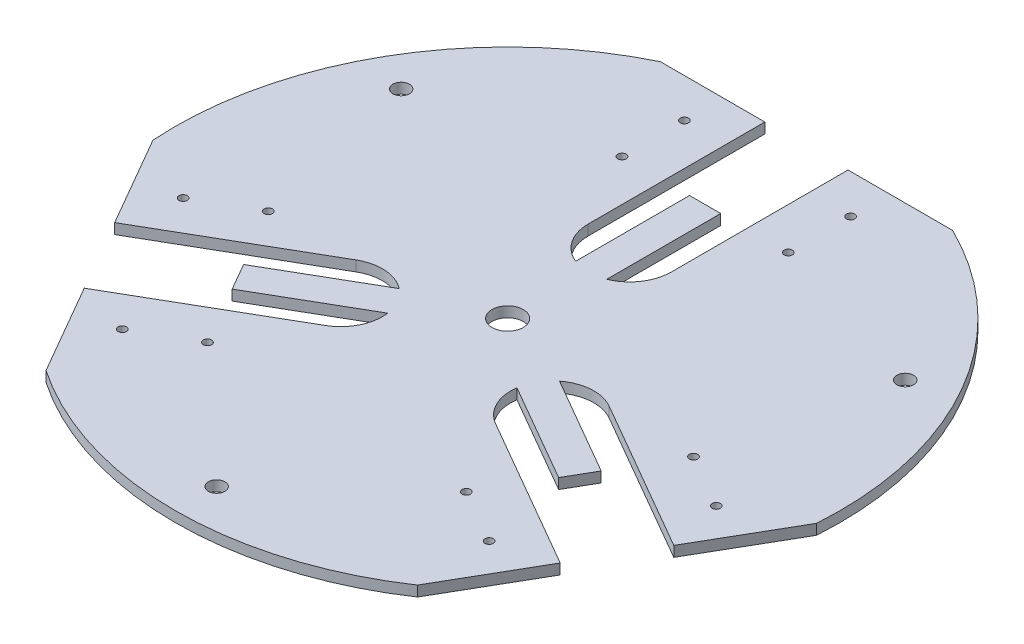
SolidWorks part; units mm, degrees
ref_plane "Front Plane" through (0, 0, 0) normal (0, 0, 1) x (1, 0, 0)
ref_plane "Top Plane" through (0, 0, 0) normal (0, 1, 0) x (1, 0, 0)
ref_plane "Right Plane" through (0, 0, 0) normal (1, 0, 0) x (0, 0, -1)
sketch "Sketch1" plane through (0, 0, 0) normal (0, 1, 0) x (1, 0, 0)
  line L0 (-20, 143.7451) -> (-20, 58.7451)
  line L1 (20, 58.7451) -> (20, 143.7451)
  line L2 (40.8747, -46.693) -> (114.4869, -89.193)
  line L3 (134.4869, -54.552) -> (60.8747, -12.052)
  line L4 (-60.8747, -12.052) -> (-134.4869, -54.552)
  line L5 (-114.4869, -89.193) -> (-40.8747, -46.693)
  line L6 (0, 204.191) -> (0, -191.6443) construction
  line L7 (116.1895, 110) -> (-116.1895, 110) construction
  line L8 (-70.2663, 143.7451) -> (-20, 143.7451)
  line L9 (159.62, -11.0201) -> (134.4869, -54.552)
  line L10 (-89.3537, -132.7249) -> (-114.4869, -89.193)
  line L11 (114.4869, -89.193) -> (89.3537, -132.7249)
  line L12 (-134.4869, -54.552) -> (-159.62, -11.0201)
  line L13 (20, 143.7451) -> (70.2663, 143.7451)
  line L14 (-7.5, 40.2046) -> (-7.5, 95)
  line L15 (-7.5, 95) -> (7.5, 95)
  line L16 (7.5, 95) -> (7.5, 40.2046)
  line L17 (38.5682, -13.6071) -> (86.0224, -41.0048)
  line L18 (78.5224, -53.9952) -> (31.0682, -26.5975)
  line L19 (86.0224, -41.0048) -> (78.5224, -53.9952)
  line L20 (-31.0682, -26.5975) -> (-78.5224, -53.9952)
  line L21 (-86.0224, -41.0048) -> (-38.5682, -13.6071)
  line L22 (-78.5224, -53.9952) -> (-86.0224, -41.0048)
  arc A0 (-70.2663, 143.7451) -> (-159.62, -11.0201) centre (0, 0) ccw
  arc A1 (-20, 58.7451) -> (-7.5, 40.2046) centre (0, 58.7451) ccw
  arc A2 (60.8747, -12.052) -> (38.5682, -13.6071) centre (50.8747, -29.3725) ccw
  arc A3 (-40.8747, -46.693) -> (-31.0682, -26.5975) centre (-50.8747, -29.3725) ccw
  arc A4 (-89.3537, -132.7249) -> (89.3537, -132.7249) centre (0, 0) ccw
  arc A5 (159.62, -11.0201) -> (70.2663, 143.7451) centre (0, 0) ccw
  circle A6 centre (40, 125) radius 2
  circle A7 centre (40, 95) radius 2
  circle A8 centre (-40, 95) radius 2
  circle A9 centre (-40, 125) radius 2
  circle A10 centre (102.2724, -12.859) radius 2
  circle A11 centre (128.2532, -27.859) radius 2
  circle A12 centre (88.2532, -97.141) radius 2
  circle A13 centre (62.2724, -82.141) radius 2
  circle A14 centre (-62.2724, -82.141) radius 2
  circle A15 centre (-88.2532, -97.141) radius 2
  circle A16 centre (-128.2532, -27.859) radius 2
  circle A17 centre (-102.2724, -12.859) radius 2
  circle A18 centre (0, -140) radius 4
  circle A19 centre (-121.2436, 70) radius 4
  circle A20 centre (121.2436, 70) radius 4
  circle A21 centre (0, 0) radius 7.5
  arc A22 (7.5, 40.2046) -> (20, 58.7451) centre (0, 58.7451) ccw
  arc A23 (-38.5682, -13.6071) -> (-60.8747, -12.052) centre (-50.8747, -29.3725) ccw
  arc A24 (31.0682, -26.5975) -> (40.8747, -46.693) centre (50.8747, -29.3725) ccw
  point P20 (0, 0)
  point P47 (0, 0)
  point P56 (0, 0)
  point P63 (0, 0)
  point P65 (0, 0)
  point P77 (0, 0)
  point P78 (0, 0)
  point P82 (0, 0)
  point P88 (0, 0)
  point P91 (0, 0)
  dimension "D1" = 160
  dimension "D5" = 4
  dimension "D6" = 4
  dimension "D11" = 8
  dimension "D14" = 15
  dimension "D2" = 40
  dimension "D3" = 15
  dimension "D7" = 20
  dimension "D8" = 110
  dimension "D9" = 30
  dimension "D12" = 7.5
  dimension "D16" = 3
  dimension "D17" = 3
  dimension "D15" = 15
  dimension "D4" = 3
  dimension "D10" = 3
  dimension "D13" = 3
extrude "Boss-Extrude1" add sketch "Sketch1" along normal blind 5
